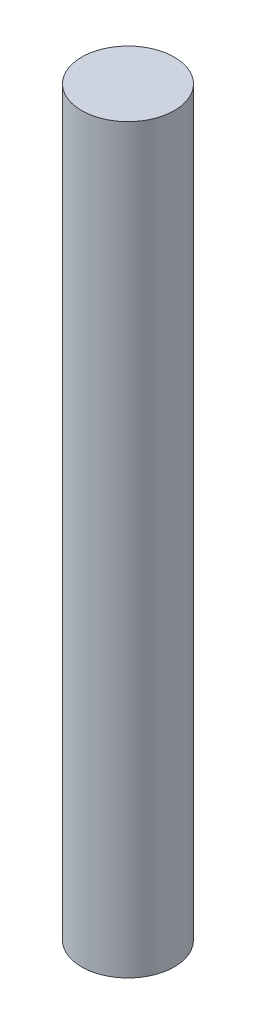
SolidWorks part; units mm, degrees
ref_plane "Front Plane" through (0, 0, 0) normal (0, 0, 1) x (1, 0, 0)
ref_plane "Top Plane" through (0, 0, 0) normal (0, 1, 0) x (1, 0, 0)
ref_plane "Right Plane" through (0, 0, 0) normal (1, 0, 0) x (0, 0, -1)
sketch "Sketch1" plane through (0, 0, 0) normal (0, 1, 0) x (1, 0, 0)
  circle A0 centre (0, 0) radius 6.35
  dimension "D1" = 12.7
extrude "Boss-Extrude1" add sketch "Sketch1" along normal blind 101.6
sketch "Sketch2" plane through (0, 101.6, 0) normal (0, 1, 0) x (1, 0, 0)
  point P0 (0, 0)
sketch "Sketch3" plane through (0, 0, 0) normal (0, -1, 0) x (1, 0, 0)
  point P0 (0, 0)
